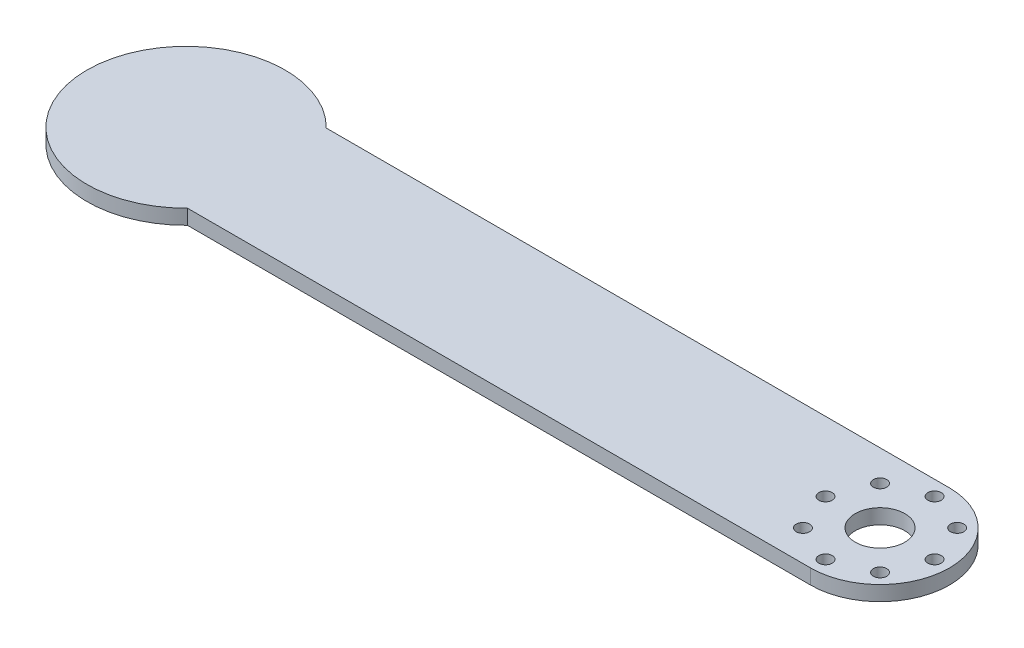
SolidWorks part; units mm, degrees
ref_plane "前视基准面" through (0, 0, 0) normal (0, 0, 1) x (1, 0, 0)
ref_plane "上视基准面" through (0, 0, 0) normal (0, 1, 0) x (1, 0, 0)
ref_plane "右视基准面" through (0, 0, 0) normal (1, 0, 0) x (0, 0, -1)
sketch "草图1" plane through (0, 0, 0) normal (0, 1, 0) x (1, 0, 0)
  line L0 (0, 14) -> (0, -14) construction
  line L1 (14.2829, -14) -> (140, -14)
  line L2 (0, 0) -> (217.9089, 0) construction
  line L3 (140, 14) -> (140, -14) construction
  line L12 (14.2829, 14) -> (140, 14)
  arc A0 (140, 14) -> (140, -14) centre (140, 0) cw
  circle A1 centre (140, 0) radius 5
  circle A2 centre (140, 0) radius 11 construction
  circle A3 centre (140, 11) radius 1.35
  circle A4 centre (147.7782, 7.7782) radius 1.35
  circle A5 centre (151, 0) radius 1.35
  circle A6 centre (147.7782, -7.7782) radius 1.35
  circle A7 centre (140, -11) radius 1.35
  circle A8 centre (132.2218, -7.7782) radius 1.35
  circle A9 centre (129, 0) radius 1.35
  circle A10 centre (132.2218, 7.7782) radius 1.35
  arc A11 (14.2829, 14) -> (14.2829, -14) centre (0, 0) ccw
  point P0 (0, 0)
  point P30 (140, 0)
  dimension "D2" = 10
  dimension "D3" = 22
  dimension "D1" = 28
  dimension "D5" = 8
  dimension "D4" = 2.7
  dimension "D7" = 40
  dimension "D6" = 140
extrude "凸台-拉伸1" add sketch "草图1" along normal blind 3
